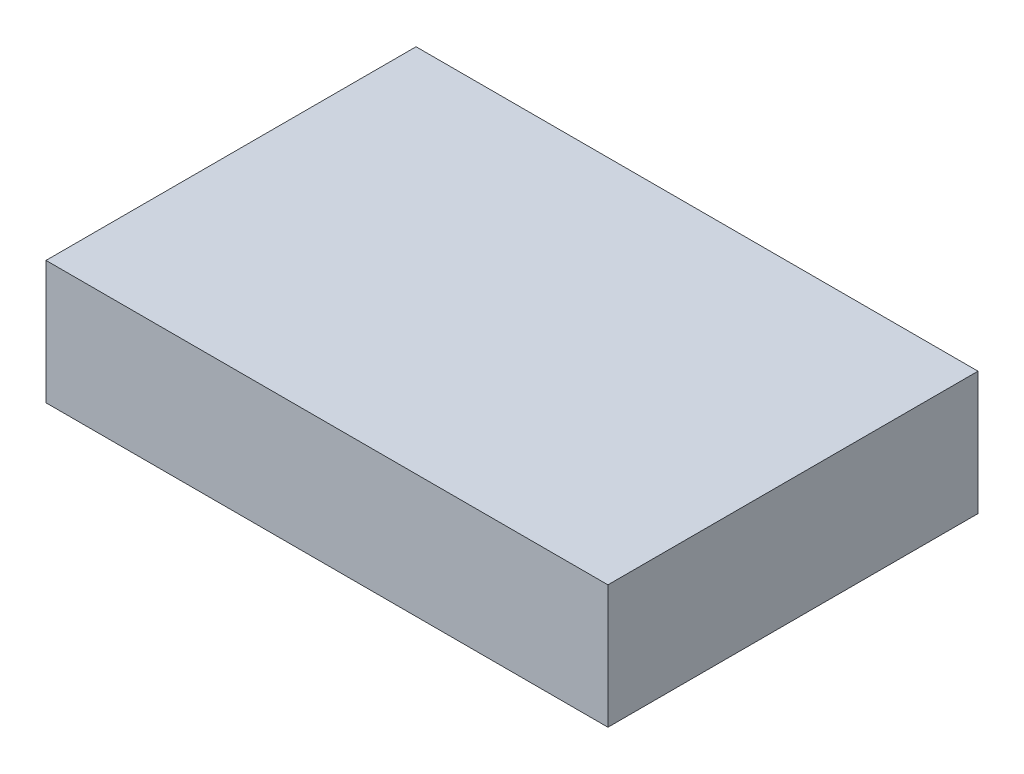
SolidWorks part; units mm, degrees
ref_plane "Plano frontal" through (0, 0, 0) normal (0, 0, 1) x (1, 0, 0)
ref_plane "Plano superior" through (0, 0, 0) normal (0, 1, 0) x (1, 0, 0)
ref_plane "Plano direito" through (0, 0, 0) normal (1, 0, 0) x (0, 0, -1)
sketch "Esboço1" plane through (0, 0, 0) normal (0, 1, 0) x (1, 0, 0)
  line L1 (-41, -27) -> (41, -27)
  line L2 (-41, -27) -> (-41, 27)
  line L3 (-41, 27) -> (41, 27)
  line L4 (41, -27) -> (41, 27)
  line L5 (-41, -27) -> (41, 27) construction
  line L6 (-41, 27) -> (41, -27) construction
  point P0 (0, 0)
  dimension "D1" = 82
  dimension "D2" = 54
extrude "Ressalto-extrusão1" add sketch "Esboço1" along normal blind 18
